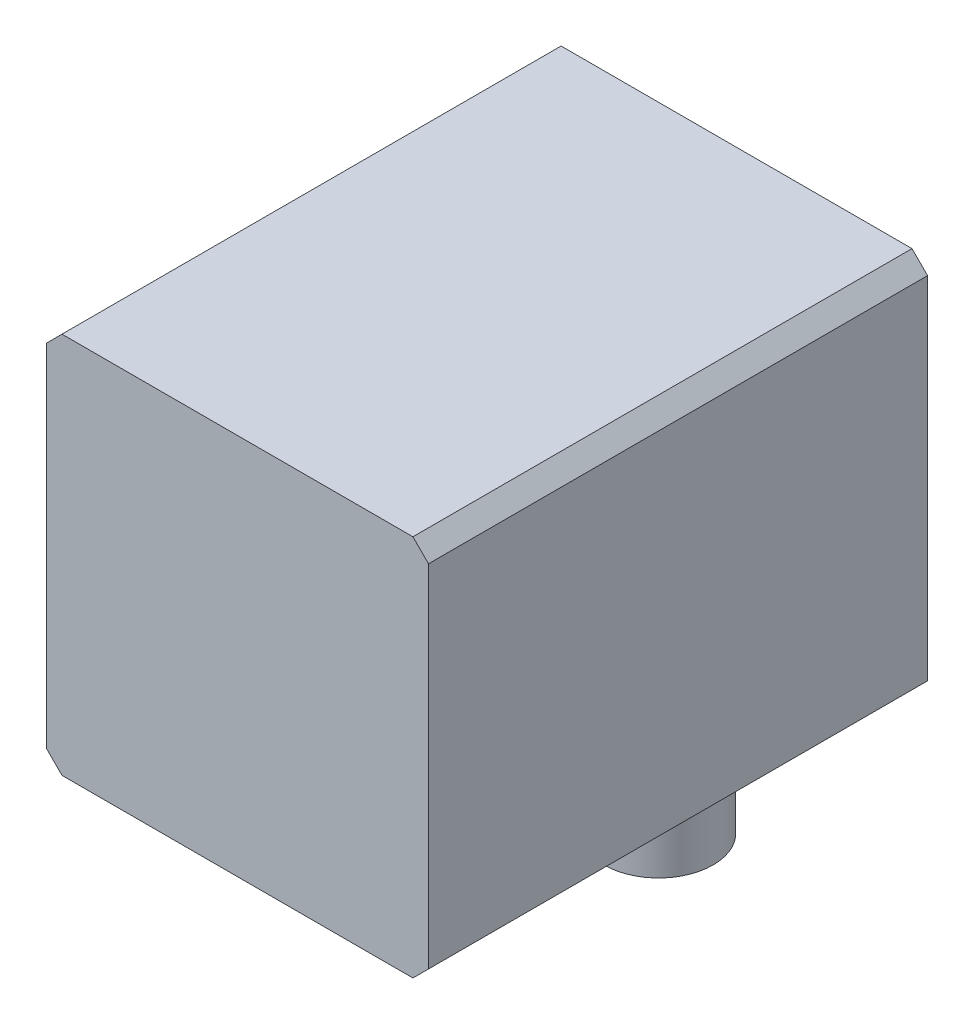
SolidWorks part; units mm, degrees
ref_plane "前视基准面" through (0, 0, 0) normal (0, 0, 1) x (1, 0, 0)
ref_plane "上视基准面" through (0, 0, 0) normal (0, 1, 0) x (1, 0, 0)
ref_plane "右视基准面" through (0, 0, 0) normal (1, 0, 0) x (0, 0, -1)
sketch "草图6" plane through (0, 0, 0) normal (0, 0, 1) x (1, 0, 0)
  line L1 (-61.25, 61.25) -> (61.25, 61.25)
  line L2 (-61.25, 61.25) -> (-61.25, -61.25)
  line L3 (-61.25, -61.25) -> (61.25, -61.25)
  line L4 (61.25, 61.25) -> (61.25, -61.25)
  dimension "D1" = 122.5
  dimension "D2" = 61.25
  dimension "D3" = 61.25
extrude "凸台-拉伸5" add sketch "草图6" along normal blind 160
sketch "草图7" plane through (0, -61.25, 0) normal (0, -1, 0) x (1, 0, 0)
  circle A0 centre (0, 25) radius 17.5
  point P2 (0, 0)
  dimension "D1" = 35
  dimension "D2" = 25
extrude "凸台-拉伸6" add sketch "草图7" along normal blind 55.5
sketch "草图8" plane through (0, -116.75, 0) normal (0, -1, 0) x (1, 0, 0)
  circle A0 centre (0, 25) radius 6
  dimension "D1" = 12
extrude "凸台-拉伸7" add sketch "草图8" along normal blind 5
chamfer "倒角1" distance 5 angle 45 4 edges at (61.25, 61.25, 80) (61.25, -61.25, 80) (-61.25, 61.25, 80) (-61.25, -61.25, 80)
sketch "草图9" plane through (0, 0, 0) normal (0, 0, -1) x (-1, 0, 0)
  line L1 (-48, 48) -> (48, 48) construction
  line L2 (-48, 48) -> (-48, -48) construction
  line L3 (-48, -48) -> (48, -48) construction
  line L4 (48, 48) -> (48, -48) construction
  circle A0 centre (-48, 48) radius 2.75
  circle A1 centre (48, 48) radius 2.75
  circle A2 centre (48, -48) radius 2.75
  circle A3 centre (-48, -48) radius 2.75
  dimension "D4" = 5.5
  dimension "D1" = 96
  dimension "D2" = 48
  dimension "D3" = 48
extrude "切除-拉伸1" cut sketch "草图9" against normal blind 20
